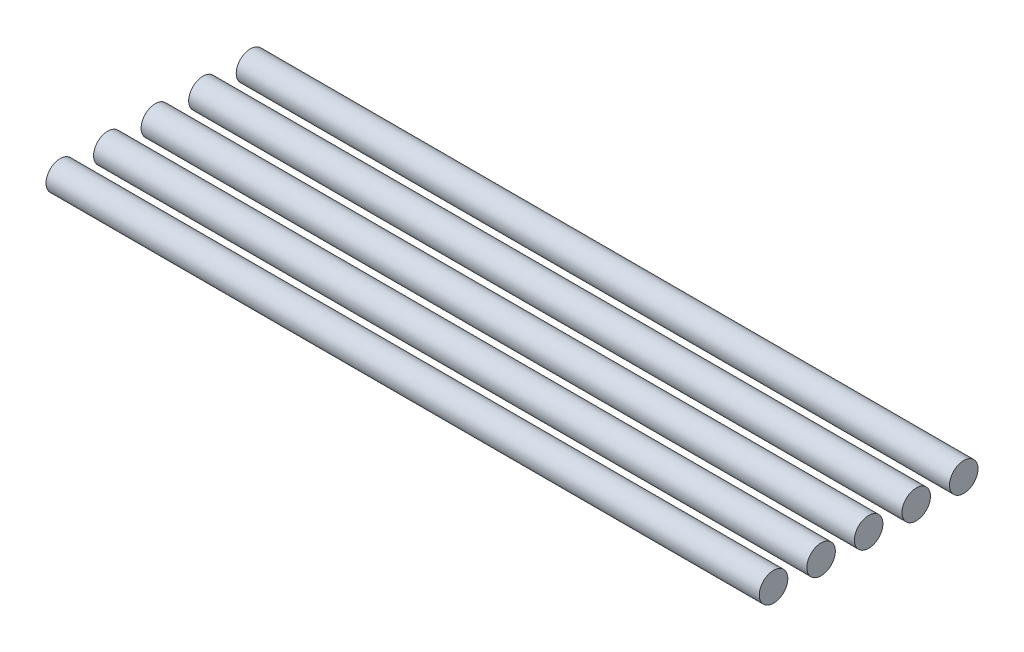
SolidWorks part; units mm, degrees
ref_plane "Front Plane" through (0, 0, 0) normal (0, 0, 1) x (1, 0, 0)
ref_plane "Top Plane" through (0, 0, 0) normal (0, 1, 0) x (1, 0, 0)
ref_plane "Right Plane" through (0, 0, 0) normal (1, 0, 0) x (0, 0, -1)
sketch "Sketch1" plane through (0, 0, 0) normal (1, 0, 0) x (0, 0, -1)
  line L0 (-5.08, 0) -> (5.08, 0) construction
  circle A0 centre (0, 0) radius 0.762
  circle A1 centre (-5.08, 0) radius 0.762
  circle A2 centre (-2.54, 0) radius 0.762
  circle A3 centre (2.54, 0) radius 0.762
  circle A4 centre (5.08, 0) radius 0.762
  dimension "D1" = 1.524
  dimension "D2" = 2.54
  dimension "D3" = 2.54
  dimension "D4" = 2.54
extrude "Boss-Extrude1" add sketch "Sketch1" along normal mid plane 38.1
